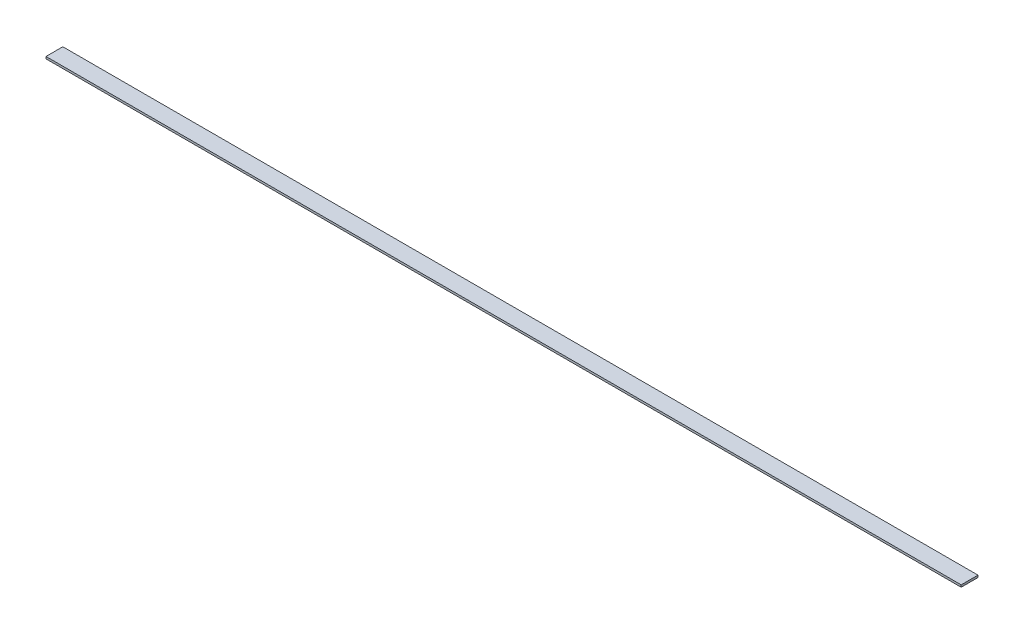
SolidWorks part; units mm, degrees
ref_plane "Front Plane" through (0, 0, 0) normal (0, 0, 1) x (1, 0, 0)
ref_plane "Top Plane" through (0, 0, 0) normal (0, 1, 0) x (1, 0, 0)
ref_plane "Right Plane" through (0, 0, 0) normal (1, 0, 0) x (0, 0, -1)
sketch "Sketch1" plane through (0, 0, 0) normal (0, 1, 0) x (1, 0, 0)
  line L1 (-544, 10) -> (544, 10)
  line L2 (-544, 10) -> (-544, -10)
  line L3 (-544, -10) -> (544, -10)
  line L4 (544, 10) -> (544, -10)
  line L5 (-544, 10) -> (544, -10) construction
  line L6 (-544, -10) -> (544, 10) construction
  point P0 (0, 0)
  dimension "D1" = 1088
  dimension "D2" = 20
extrude "Boss-Extrude1" add sketch "Sketch1" along normal blind 2.5
